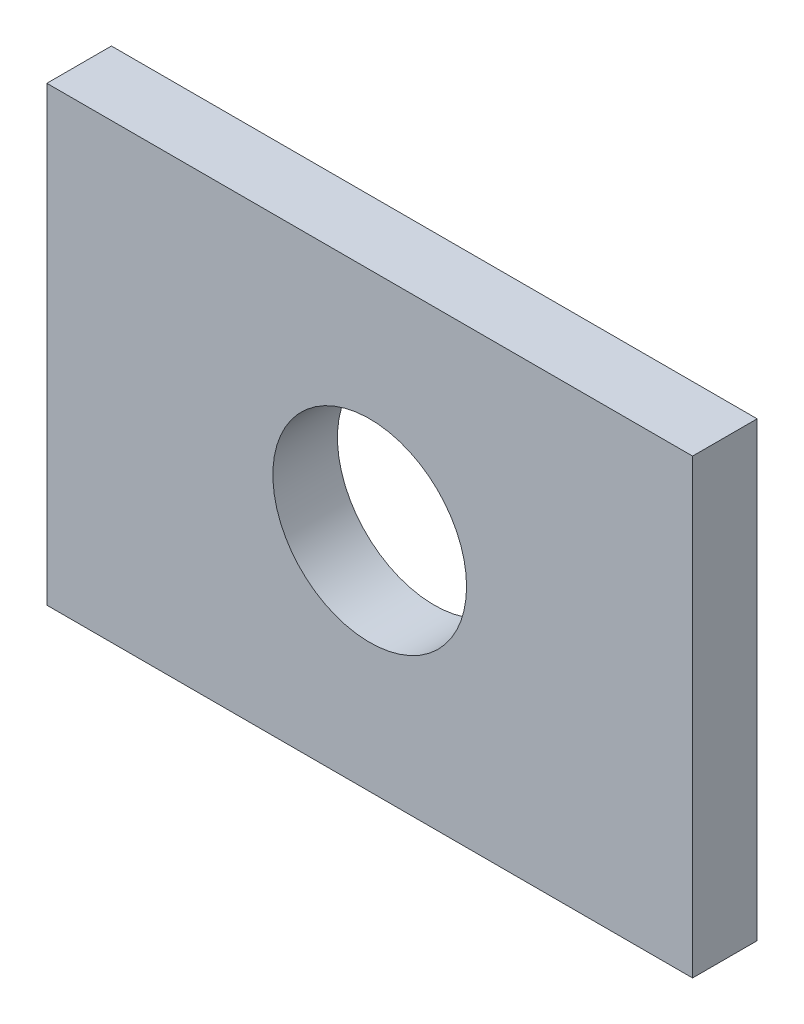
SolidWorks part; units mm, degrees
ref_plane "前视基准面" through (0, 0, 0) normal (0, 0, 1) x (1, 0, 0)
ref_plane "上视基准面" through (0, 0, 0) normal (0, 1, 0) x (1, 0, 0)
ref_plane "右视基准面" through (0, 0, 0) normal (1, 0, 0) x (0, 0, -1)
other "Configuration Table"
sketch "草图1" plane through (0, 0, 0) normal (0, 0, 1) x (1, 0, 0)
  line L1 (-5, 3.5) -> (5, 3.5)
  line L2 (-5, 3.5) -> (-5, -3.5)
  line L3 (-5, -3.5) -> (5, -3.5)
  line L4 (5, 3.5) -> (5, -3.5)
  line L5 (-5, 3.5) -> (5, -3.5) construction
  line L6 (-5, -3.5) -> (5, 3.5) construction
  circle A0 centre (0, 0) radius 1.5
  point P0 (0, 0)
  point P7 (0, 0)
  point P8 (0, 0)
  dimension "D3" = 3
  dimension "D1" = 10
  dimension "D2" = 7
extrude "凸台-拉伸1" add sketch "草图1" along normal blind 1
